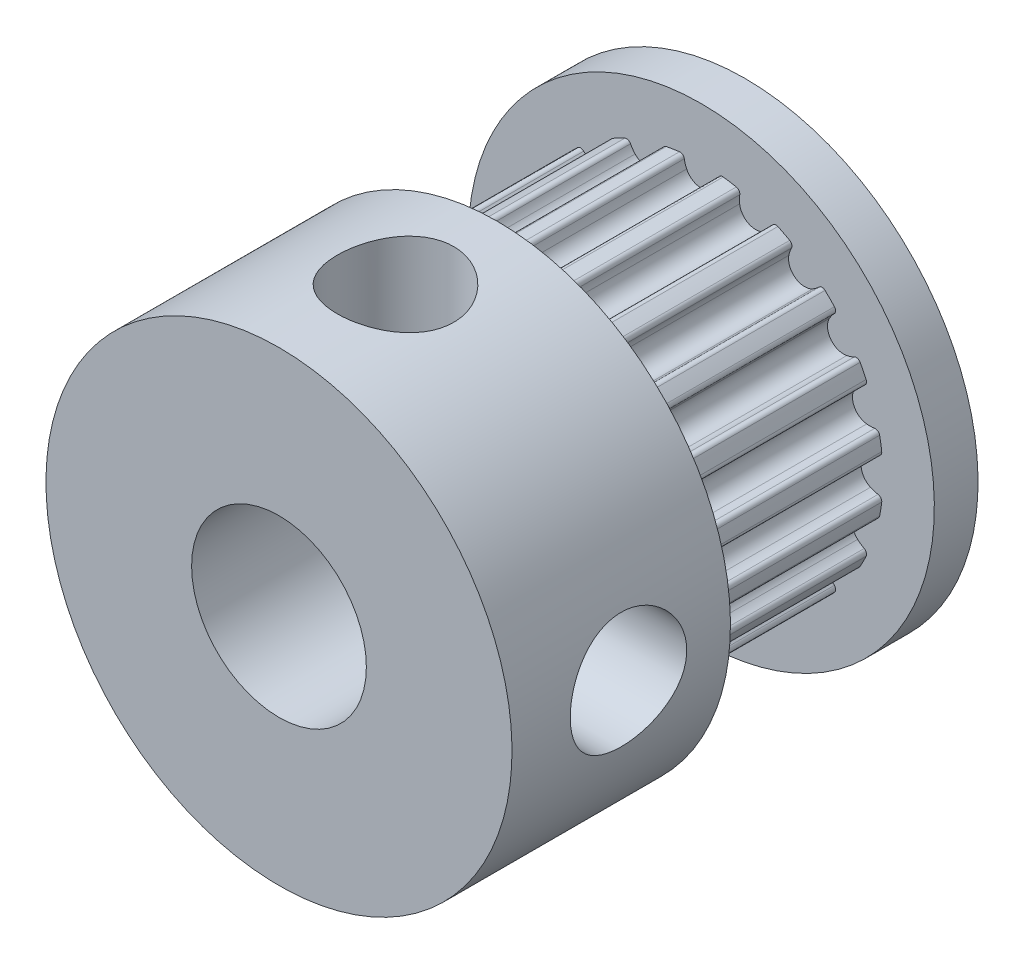
SolidWorks part; units mm, degrees
material "Aleación 6061"
ref_plane "Alzado" through (0, 0, 0) normal (0, 0, 1) x (1, 0, 0)
ref_plane "Planta" through (0, 0, 0) normal (0, 1, 0) x (1, 0, 0)
ref_plane "Vista lateral" through (0, 0, 0) normal (1, 0, 0) x (0, 0, -1)
sketch "Croquis1" plane through (0, 0, 0) normal (0, 0, 1) x (1, 0, 0)
  circle A0 centre (0, 0) radius 6.366
  dimension "D1" = 12.732
extrude "Saliente-Extruir1" add sketch "Croquis1" along normal blind 7
sketch "Croquis3" plane through (0, 0, 0) normal (0, 0, -1) x (-1, 0, 0)
  line L0 (0, 0) -> (0, 6.239) construction
  line L1 (0, 0) -> (0.976, 6.1622) construction
  line L2 (0.976, 6.1622) -> (0, 0) construction
  line L3 (0, 0) -> (-0.976, 6.1622) construction
  line L6 (0.976, 6.1622) -> (0.9959, 6.2876)
  line L8 (-0.976, 6.1622) -> (-0.9959, 6.2876)
  arc A0 (-0.7498, 6.1938) -> (-0.976, 6.1622) centre (0, 0) ccw
  arc A1 (-0.5037, 5.8059) -> (0.5037, 5.8059) centre (0, 6.039) ccw
  arc A2 (-0.5837, 6.0685) -> (-0.5037, 5.8059) centre (0.4038, 6.2259) ccw
  arc A3 (-0.5837, 6.0685) -> (-0.7498, 6.1938) centre (-0.7318, 6.0449) ccw
  arc A4 (0.5837, 6.0685) -> (0.5037, 5.8059) centre (-0.4038, 6.2259) cw
  arc A5 (0.5837, 6.0685) -> (0.7498, 6.1938) centre (0.7318, 6.0449) cw
  arc A6 (0.7498, 6.1938) -> (0.976, 6.1622) centre (0, 0) cw
  circle A7 centre (0, 0) radius 6.366 construction
  circle A11 centre (0, 0) radius 6.366
  circle M8 centre (0, 0) radius 6.366
  dimension "D1" = 6.239
  dimension "D4" = 1.11
  dimension "D5" = 2
  dimension "D7" = 0.3
  dimension "D3" = 18
  dimension "D6" = 0.2
extrude "Cortar-Extruir1" cut sketch "Croquis3" against normal through all contours A5 A6 L6 L8 A0 A3 A2 A1 A4 M8
pattern_circular "MatrizC1" count 20 over 360 about axis through (0, 0, 0) along (0, 0, 1) of "Cortar-Extruir1"
sketch "Croquis5" plane through (0, 0, 0) normal (1, 0, 0) x (0, 0, -1)
  line L0 (0, 0) -> (1.5, 0)
  line L1 (0, -0.5037) -> (0, 0.5037) construction
  line L2 (1.5, 0) -> (1.5, 8)
  line L3 (1.5, 8) -> (0, 8)
  line L4 (0, 8) -> (0, 0)
  line L5 (-7, 0) -> (-14.5, 0)
  line L6 (-7, 0.5037) -> (-7, -0.5037) construction
  line L7 (-14.5, 0) -> (-14.5, 8)
  line L8 (-14.5, 8) -> (-7, 8)
  line L10 (-7, 0) -> (-7, 8)
  dimension "D1" = 8
  dimension "D2" = 1.5
  dimension "D3" = 8
  dimension "D4" = 7.5
revolve "Revolución1" add sketch "Croquis5" angle 360 about L5
sketch "Croquis6" plane through (0, 0, 14.5) normal (0, 0, 1) x (1, 0, 0)
  circle A0 centre (0, 0) radius 3
  dimension "D1" = 6
extrude "Cortar-Extruir2" cut sketch "Croquis6" against normal through all
sketch "Croquis8" plane through (0, 0, 0) normal (0, 1, 0) x (1, 0, 0)
  line L0 (-8, -7) -> (-8, -14.5) construction
  line L1 (0.5037, -7) -> (-0.5037, -7) construction
  circle A0 centre (0, -10.5) radius 2
  dimension "D1" = 4
  dimension "D2" = 8
  dimension "D3" = 3.5
extrude "Cortar-Extruir3" cut sketch "Croquis8" along normal through all
sketch "Croquis9" plane through (0, 0, 0) normal (1, 0, 0) x (0, 0, -1)
  line L0 (-14.5, -8) -> (-7, -8) construction
  line L3 (-7, -0.5037) -> (-7, 0.5037) construction
  circle A0 centre (-10.5, 0) radius 2
  dimension "D1" = 4
  dimension "D2" = 8
  dimension "D3" = 3.5
extrude "Cortar-Extruir4" cut sketch "Croquis9" along normal through all
